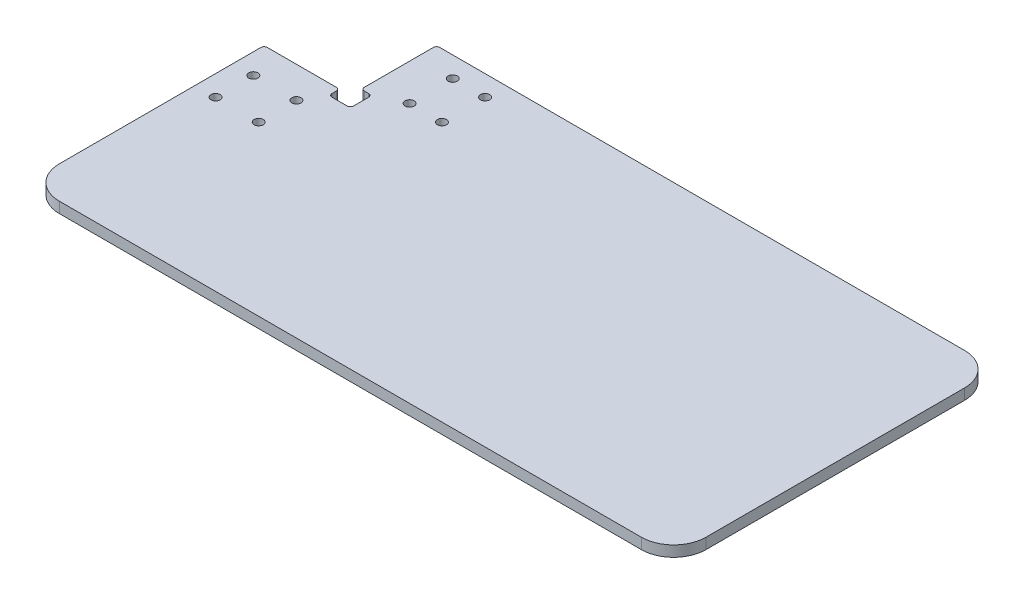
SolidWorks part; units mm, degrees
ref_plane "前视基准面" through (0, 0, 0) normal (0, 0, 1) x (1, 0, 0)
ref_plane "上视基准面" through (0, 0, 0) normal (0, 1, 0) x (1, 0, 0)
ref_plane "右视基准面" through (0, 0, 0) normal (1, 0, 0) x (0, 0, -1)
other "Configuration Table"
sketch "草图1" plane through (0, 0, 0) normal (0, 1, 0) x (1, 0, 0)
  line L0 (80, 0) -> (80, -70)
  line L1 (80, 0) -> (600, 0)
  line L2 (0, -80) -> (0, -300)
  line L3 (0, -300) -> (600, -300)
  line L4 (600, 0) -> (600, -300)
  line L5 (70, -80) -> (0, -80)
  line L6 (80, -70) -> (90, -70)
  line L7 (90, -70) -> (90, -90)
  line L8 (90, -90) -> (70, -90)
  line L9 (70, -90) -> (70, -80)
  line L10 (0, 0) -> (166.1856, -166.1856) construction
  circle A0 centre (144, -19) radius 4.25
  circle A1 centre (114, -19) radius 4.25
  circle A2 centre (144, -59) radius 4.25
  circle A3 centre (114, -59) radius 4.25
  circle A8 centre (19, -109) radius 4.25
  circle A9 centre (59, -109) radius 4.25
  circle A10 centre (19, -144) radius 4.25
  circle A11 centre (59, -144) radius 4.25
  point P30 (0, 0)
  point P31 (0, 0)
  point P32 (0, 0)
  point P33 (0, 0)
  point P34 (59.6141, -144)
  dimension "D5" = 8.5
  dimension "D15" = 8.5
  dimension "D1" = 300
  dimension "D2" = 600
  dimension "D3" = 80
  dimension "D4" = 80
  dimension "D6" = 19
  dimension "D7" = 40
  dimension "D8" = 30
  dimension "D9" = 10
  dimension "D10" = 20
  dimension "D11" = 10
  dimension "D12" = 20
  dimension "D13" = 64
  dimension "D14" = 45
  dimension "D16" = 35
  dimension "D17" = 40
  dimension "D18" = 64
  dimension "D19" = 19
extrude "凸台-拉伸1" add sketch "草图1" along normal blind 10
fillet "圆角1" radius 30 3 edges at (600, 5, 0) (0, 5, 300) (600, 5, 300)
fillet "圆角2" radius 3 7 edges at (90, 5, 70) (90, 5, 90) (70, 5, 90) (70, 5, 80) (80, 5, 70) (80, 5, 0) (0, 5, 80)
